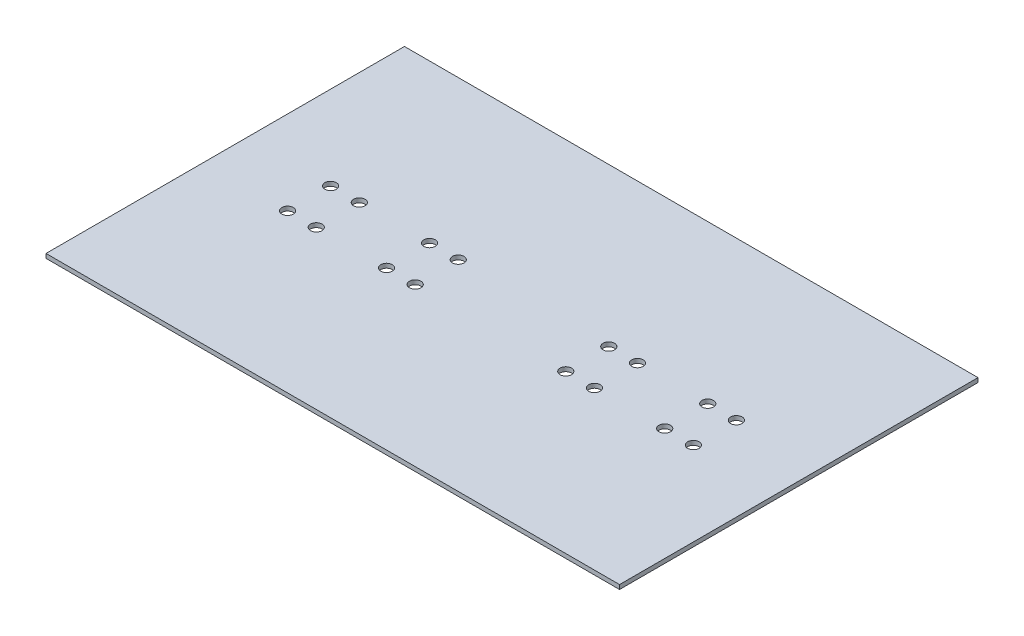
SolidWorks part; units mm, degrees
ref_plane "Front Plane" through (0, 0, 0) normal (0, 0, 1) x (1, 0, 0)
ref_plane "Top Plane" through (0, 0, 0) normal (0, 1, 0) x (1, 0, 0)
ref_plane "Right Plane" through (0, 0, 0) normal (1, 0, 0) x (0, 0, -1)
sketch "Sketch1" plane through (0, 0, 0) normal (0, 1, 0) x (1, 0, 0)
  line L1 (-200, -125) -> (200, -125)
  line L2 (-200, -125) -> (-200, 125)
  line L3 (-200, 125) -> (200, 125)
  line L4 (200, -125) -> (200, 125)
  line L5 (-200, -125) -> (200, 125) construction
  line L6 (-200, 125) -> (200, -125) construction
  point P0 (0, 0)
  dimension "D1" = 400
  dimension "D2" = 250
extrude "Boss-Extrude1" add sketch "Sketch1" along normal blind 3
sketch "Sketch2" plane through (0, 3, 0) normal (0, 1, 0) x (1, 0, 0)
  line L0 (0, 125) -> (0, -125) construction
  line L1 (200, 125) -> (-200, 125) construction
  line L2 (-200, -125) -> (200, -125) construction
  line L3 (-200, 0) -> (200, 0) construction
  line L4 (-200, 125) -> (-200, -125) construction
  line L5 (200, -125) -> (200, 125) construction
  line L6 (99, -125) -> (99, 125) construction
  circle A18 centre (121.5, 15) radius 4
  circle A19 centre (141.5, 15) radius 4
  circle A20 centre (121.5, -15) radius 4
  circle A21 centre (141.5, -15) radius 4
  circle A22 centre (72.5, 15) radius 4
  circle A23 centre (52.5, 15) radius 4
  circle A24 centre (72.5, -15) radius 4
  circle A25 centre (52.5, -15) radius 4
  circle A26 centre (-52.5, -15) radius 4
  circle A27 centre (-72.5, -15) radius 4
  circle A28 centre (-52.5, 15) radius 4
  circle A29 centre (-72.5, 15) radius 4
  circle A30 centre (-141.5, -15) radius 4
  circle A31 centre (-121.5, -15) radius 4
  circle A32 centre (-141.5, 15) radius 4
  circle A33 centre (-121.5, 15) radius 4
  dimension "D3" = 8
  dimension "D5" = 8
  dimension "D6" = 30
  dimension "D7" = 20
  dimension "D8" = 20
  dimension "D9" = 30
  dimension "D10" = 58.5
  dimension "D11" = 110
  dimension "D4" = 49
  dimension "D12" = 20
  dimension "D13" = 30
extrude "Cut-Extrude1" cut sketch "Sketch2" against normal through all
